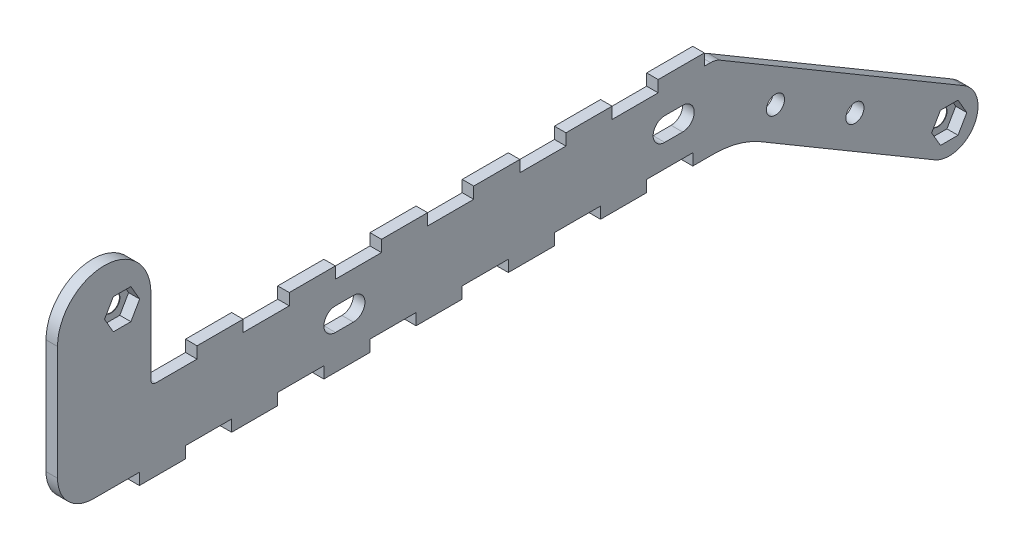
SolidWorks part; units mm, degrees
material "Acrylic (Medium-high impact)"
ref_plane "Front Plane" through (0, 0, 0) normal (0, 0, 1) x (1, 0, 0)
ref_plane "Top Plane" through (0, 0, 0) normal (0, 1, 0) x (1, 0, 0)
ref_plane "Right Plane" through (0, 0, 0) normal (1, 0, 0) x (0, 0, -1)
sketch "Sketch1" plane through (0, 0, 0) normal (1, 0, 0) x (0, 0, -1)
  line L0 (227.7787, -69.4291) -> (0, 0) construction
  line L1 (-7.9375, 0) -> (-7.9375, -44.45)
  line L2 (4.7625, -44.45) -> (17.4625, -44.45)
  line L3 (223.7429, -76.264) -> (169.8625, -44.45)
  line L4 (7.9375, 0) -> (7.9375, -19.05)
  line L5 (20.6375, -19.05) -> (33.3375, -19.05)
  line L6 (231.8144, -62.5941) -> (163.4451, -22.225)
  line L7 (33.3375, -19.05) -> (33.3375, -22.225)
  line L9 (7.9375, -19.05) -> (7.9375, -22.225)
  line L10 (7.9375, -22.225) -> (20.6375, -22.225)
  line L11 (20.6375, -19.05) -> (20.6375, -22.225)
  line L12 (33.3375, -22.225) -> (46.0375, -22.225)
  line L13 (46.0375, -19.05) -> (46.0375, -22.225)
  line L14 (58.7375, -19.05) -> (58.7375, -22.225)
  line L15 (58.7375, -22.225) -> (71.4375, -22.225)
  line L16 (71.4375, -19.05) -> (71.4375, -22.225)
  line L17 (84.1375, -19.05) -> (84.1375, -22.225)
  line L18 (84.1375, -22.225) -> (96.8375, -22.225)
  line L19 (96.8375, -19.05) -> (96.8375, -22.225)
  line L20 (109.5375, -19.05) -> (109.5375, -22.225)
  line L21 (109.5375, -22.225) -> (122.2375, -22.225)
  line L22 (122.2375, -19.05) -> (122.2375, -22.225)
  line L23 (134.9375, -19.05) -> (134.9375, -22.225)
  line L24 (134.9375, -22.225) -> (147.6375, -22.225)
  line L25 (122.2375, -19.05) -> (134.9375, -19.05)
  line L26 (96.8375, -19.05) -> (109.5375, -19.05)
  line L27 (147.6375, -19.05) -> (147.6375, -22.225) [skipped]
  line L28 (71.4375, -19.05) -> (84.1375, -19.05)
  line L29 (46.0375, -19.05) -> (58.7375, -19.05)
  line L30 (-7.9375, -44.45) -> (-7.9375, -41.275)
  line L32 (-7.9375, -44.45) -> (-7.9375, -41.275)
  line L33 (-7.9375, -41.275) -> (4.7625, -41.275)
  line L34 (4.7625, -44.45) -> (4.7625, -41.275)
  line L35 (17.4625, -44.45) -> (17.4625, -41.275)
  line L36 (17.4625, -41.275) -> (30.1625, -41.275)
  line L37 (30.1625, -44.45) -> (30.1625, -41.275)
  line L38 (42.8625, -44.45) -> (42.8625, -41.275)
  line L39 (42.8625, -41.275) -> (55.5625, -41.275)
  line L40 (55.5625, -44.45) -> (55.5625, -41.275)
  line L41 (68.2625, -44.45) -> (68.2625, -41.275)
  line L42 (68.2625, -41.275) -> (80.9625, -41.275)
  line L43 (80.9625, -44.45) -> (80.9625, -41.275)
  line L44 (93.6625, -44.45) -> (93.6625, -41.275)
  line L45 (93.6625, -41.275) -> (106.3625, -41.275)
  line L46 (106.3625, -44.45) -> (106.3625, -41.275)
  line L47 (119.0625, -44.45) -> (119.0625, -41.275)
  line L48 (119.0625, -41.275) -> (131.7625, -41.275)
  line L49 (131.7625, -44.45) -> (131.7625, -41.275)
  line L50 (30.1625, -44.45) -> (42.8625, -44.45)
  line L51 (55.5625, -44.45) -> (68.2625, -44.45)
  line L52 (80.9625, -44.45) -> (93.6625, -44.45)
  line L53 (106.3625, -44.45) -> (119.0625, -44.45)
  line L54 (131.7625, -44.45) -> (169.8625, -44.45)
  line L55 (147.6375, -19.05) -> (147.6375, -22.225)
  line L56 (17.4625, -44.45) -> (17.4625, -41.275)
  line L57 (147.6375, -19.05) -> (160.3375, -19.05)
  line L58 (17.4625, -41.275) -> (30.1625, -41.275)
  line L59 (30.1625, -44.45) -> (30.1625, -41.275)
  line L60 (42.8625, -44.45) -> (42.8625, -41.275)
  line L61 (42.8625, -41.275) -> (55.5625, -41.275)
  line L62 (55.5625, -44.45) -> (55.5625, -41.275)
  line L63 (68.2625, -44.45) -> (68.2625, -41.275)
  line L64 (68.2625, -41.275) -> (80.9625, -41.275)
  line L65 (80.9625, -44.45) -> (80.9625, -41.275)
  line L66 (93.6625, -44.45) -> (93.6625, -41.275)
  line L67 (93.6625, -41.275) -> (106.3625, -41.275)
  line L68 (106.3625, -44.45) -> (106.3625, -41.275)
  line L69 (119.0625, -44.45) -> (119.0625, -41.275)
  line L70 (119.0625, -41.275) -> (131.7625, -41.275)
  line L71 (131.7625, -44.45) -> (131.7625, -41.275)
  line L72 (144.4625, -44.45) -> (144.4625, -41.275)
  line L73 (144.4625, -41.275) -> (157.1625, -41.275)
  line L74 (157.1625, -44.45) -> (157.1625, -41.275)
  line L75 (160.3375, -19.05) -> (160.3375, -22.225)
  line L76 (160.3375, -22.225) -> (163.4451, -22.225)
  line L78 (-17.78, -31.4325) -> (-17.78, 0)
  circle A0 centre (0, 0) radius 2.4384
  circle A1 centre (227.7787, -69.4291) radius 2.4384
  circle A2 centre (0, 0) radius 7.9375
  circle A3 centre (227.7787, -69.4291) radius 7.9375
  arc A4 (7.9375, 0) -> (0, 7.9375) centre (0, 0) ccw
  arc A6 (-17.78, -31.4325) -> (-7.9375, -41.275) centre (-7.9375, -31.4325) ccw
  arc A7 (7.9375, 0) -> (-17.78, 0) centre (-4.9213, 0) ccw
  dimension "D1" = 4.8768
  dimension "D3" = 15.875
  dimension "D2" = 238.125
  dimension "D4" = 25.4
  dimension "D5" = 149.44
  dimension "D6" = 15.875
  dimension "D7" = 44.45
  dimension "D8" = 177.8
  dimension "D9" = 12.7
  dimension "D10" = 3.175
  dimension "D12" = 12.7
  dimension "D13" = 12.7
  dimension "D14" = 3.175
  dimension "D16" = 12.7
  dimension "D18" = 12.7
  dimension "D20" = 12.7
  dimension "D21" = 17.78
  dimension "D11" = 6
  dimension "D15" = 6
  dimension "D17" = 7
  dimension "D19" = 2
extrude "Boss-Extrude1" add sketch "Sketch1" along normal blind 3.175
sketch "Sketch2" plane through (3.175, 0, 0) normal (1, 0, 0) x (0, 0, -1)
  line L1 (2.4197, 4.191) -> (-2.4197, 4.191)
  line L2 (-2.4197, 4.191) -> (-4.8393, 0)
  line L3 (-4.8393, 0) -> (-2.4197, -4.191)
  line L4 (-2.4197, -4.191) -> (2.4197, -4.191)
  line L5 (2.4197, -4.191) -> (4.8393, 0)
  line L6 (4.8393, 0) -> (2.4197, 4.191)
  circle A0 centre (0, 0) radius 4.191 construction
  circle A1 centre (0, 0) radius 2.4384
  dimension "D1" = 8.382
  dimension "D2" = 4.8768
extrude "Cut-Extrude1" cut sketch "Sketch2" against normal blind 3.048
sketch "Sketch3" plane through (3.175, 0, 0) normal (1, 0, 0) x (0, 0, -1)
  line L1 (230.1983, -65.2381) -> (225.359, -65.2381)
  line L2 (225.359, -65.2381) -> (222.9393, -69.4291)
  line L3 (222.9393, -69.4291) -> (225.359, -73.6201)
  line L4 (225.359, -73.6201) -> (230.1983, -73.6201)
  line L5 (230.1983, -73.6201) -> (232.618, -69.4291)
  line L6 (232.618, -69.4291) -> (230.1983, -65.2381)
  circle A0 centre (227.7787, -69.4291) radius 4.191 construction
  circle A1 centre (227.7787, -69.4291) radius 2.4384
  dimension "D1" = 8.382
  dimension "D2" = 4.8768
extrude "Cut-Extrude2" cut sketch "Sketch3" against normal blind 3.048
sketch "Sketch4" [suppressed] plane through (0, 0, 0) normal (-1, 0, 0) x (0, 0, 1)
  line L1 (2.4197, 4.191) -> (-2.4197, 4.191)
  line L2 (-2.4197, 4.191) -> (-4.8393, 0)
  line L3 (-4.8393, 0) -> (-2.4197, -4.191)
  line L4 (-2.4197, -4.191) -> (2.4197, -4.191)
  line L5 (2.4197, -4.191) -> (4.8393, 0)
  line L6 (4.8393, 0) -> (2.4197, 4.191)
  circle A0 centre (0, 0) radius 4.191 construction
  circle A1 centre (0, 0) radius 2.4384
  dimension "D1" = 8.382
  dimension "D2" = 4.8768
extrude "Cut-Extrude3" [suppressed] cut sketch "Sketch4" against normal blind 3.048
sketch "Sketch5" [suppressed] plane through (0, 0, 0) normal (-1, 0, 0) x (0, 0, 1)
  line L1 (-225.359, -65.2381) -> (-230.1983, -65.2381)
  line L2 (-230.1983, -65.2381) -> (-232.618, -69.4291)
  line L3 (-232.618, -69.4291) -> (-230.1983, -73.6201)
  line L4 (-230.1983, -73.6201) -> (-225.359, -73.6201)
  line L5 (-225.359, -73.6201) -> (-222.9393, -69.4291)
  line L6 (-222.9393, -69.4291) -> (-225.359, -65.2381)
  circle A0 centre (-227.7787, -69.4291) radius 4.191 construction
  circle A1 centre (-227.7787, -69.4291) radius 2.4384
  dimension "D1" = 8.382
  dimension "D2" = 4.8768
extrude "Cut-Extrude4" [suppressed] cut sketch "Sketch5" against normal blind 3.048
sketch "Sketch6" [suppressed] plane through (3.175, 0, 0) normal (1, 0, 0) x (0, 0, -1)
  line L0 (179.9339, -41.1789) -> (201.8058, -54.0932) construction
  line L1 (231.8144, -62.5941) -> (163.4451, -22.225) construction
  line L2 (227.7787, -69.4291) -> (222.9146, -66.5571) construction
  circle A1 centre (227.7787, -69.4291) radius 2.4384 construction
  circle A2 centre (227.7787, -69.4291) radius 2.4384 construction
  circle A3 centre (201.8058, -54.0932) radius 2.5019
  circle A4 centre (179.9339, -41.1789) radius 2.5019
  dimension "D3" = 5.0038
  dimension "D1" = 25.4
  dimension "D2" = 30.1625
extrude "Cut-Extrude5" [suppressed] cut sketch "Sketch6" against normal through all
sketch "Sketch7" plane through (0, 0, 0) normal (-1, 0, 0) x (0, 0, 1)
  line L0 (-227.7787, -69.4291) -> (-220.1081, -64.8999) construction
  line L1 (-201.8058, -54.0932) -> (-179.9339, -41.1789) construction
  line L2 (-231.8144, -62.5941) -> (-163.4451, -22.225) construction
  circle A0 centre (-227.7787, -69.4291) radius 2.4384 construction
  circle A1 centre (-227.7787, -69.4291) radius 2.4384 construction
  circle A2 centre (-201.8058, -54.0932) radius 2.5019
  circle A3 centre (-179.9339, -41.1789) radius 2.5019
  dimension "D3" = 5.0038
  dimension "D1" = 25.4
  dimension "D2" = 30.1625
extrude "Cut-Extrude6" cut sketch "Sketch7" against normal through all
sketch "Sketch9" plane through (3.175, 0, 0) normal (1, 0, 0) x (0, 0, -1)
  line L3 (58.7489, -31.75) -> (63.6994, -31.75) construction
  line L4 (58.7489, -28.575) -> (63.6994, -28.575)
  line L5 (58.7489, -34.925) -> (63.6994, -34.925)
  line L6 (46.0375, -22.225) -> (46.0375, -41.275) construction
  line L8 (42.8625, -41.275) -> (55.5625, -41.275) construction
  line L9 (-17.78, -31.4325) -> (-17.78, 0) construction
  line L10 (154.3749, -28.575) -> (149.4244, -28.575)
  line L11 (149.4244, -34.925) -> (154.3749, -34.925)
  line L13 (154.3749, -31.75) -> (149.4244, -31.75) construction
  arc A2 (58.7489, -28.575) -> (58.7489, -34.925) centre (58.7489, -31.75) ccw
  arc A3 (63.6994, -34.925) -> (63.6994, -28.575) centre (63.6994, -31.75) ccw
  arc A4 (149.4244, -28.575) -> (149.4244, -34.925) centre (149.4244, -31.75) ccw
  arc A5 (154.3749, -34.925) -> (154.3749, -28.575) centre (154.3749, -31.75) ccw
  point P0 (0, 0)
  point P9 (61.2242, -31.75)
  point P17 (46.0375, -31.75)
  point P28 (151.8996, -31.75)
  point P29 (0, 0)
  dimension "D7" = 3.175
  dimension "D4" = 3.175
  dimension "D5" = 79.0042
  dimension "D6" = 4.9505
  dimension "D8" = 4.9505
  dimension "D9" = 169.6796
extrude "Cut-Extrude7" cut sketch "Sketch9" against normal up to surface (3.175 mm away) up to face at (0, -54.0932, -199.3039)
fillet "Fillet1" radius 25.4 1 edges at (1.5875, -44.45, -169.8625)
fillet "Fillet2" radius 1.27 1 edges at (1.5875, -22.225, -7.9375)
fillet "Fillet3" [suppressed] radius 25.4
fillet "Fillet4" [suppressed] radius 5.08
fillet "Fillet5" radius 5.08 1 edges at (1.5875, -22.225, -163.4451)
